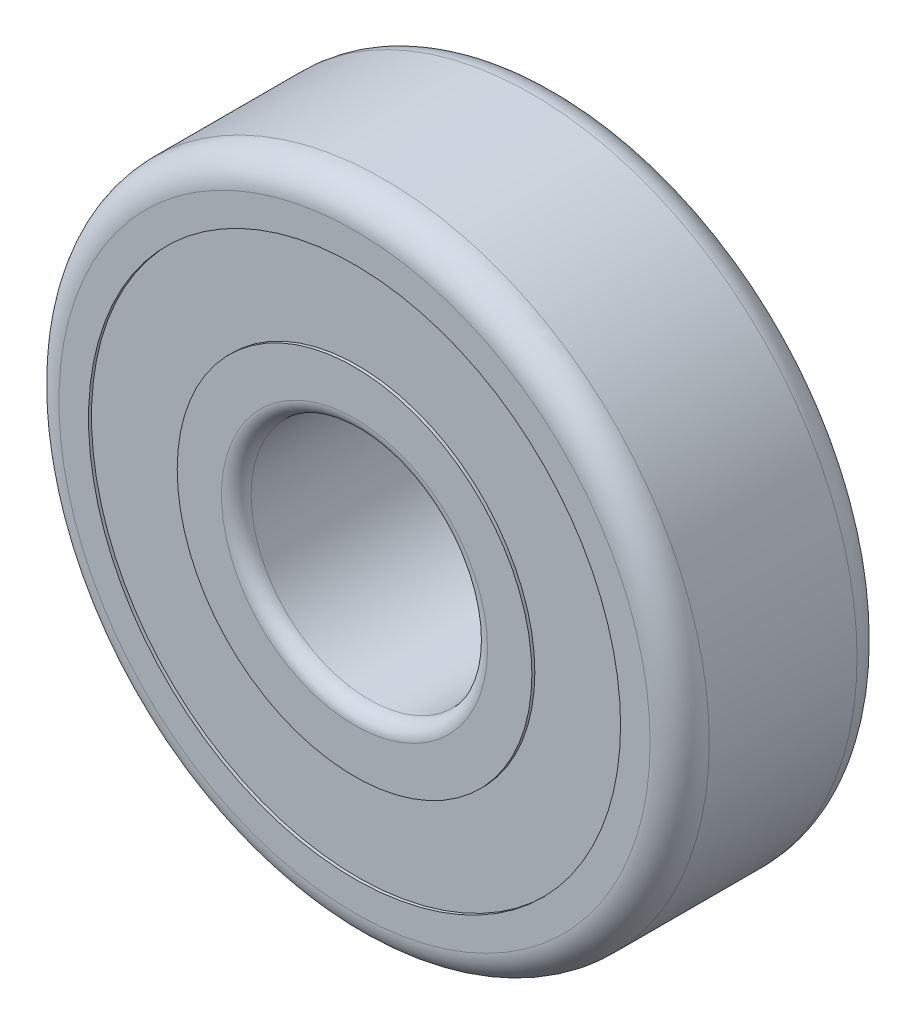
SolidWorks part; units mm, degrees
material "AISI 304"
ref_plane "Front Plane" through (0, 0, 0) normal (0, 0, 1) x (1, 0, 0)
ref_plane "Top Plane" through (0, 0, 0) normal (0, 1, 0) x (1, 0, 0)
ref_plane "Right Plane" through (0, 0, 0) normal (1, 0, 0) x (0, 0, -1)
sketch "Sketch1" plane through (0, 0, 0) normal (0, 0, 1) x (1, 0, 0)
  circle A0 centre (0, 0) radius 11
  circle A1 centre (0, 0) radius 4
  dimension "D1" = 22
  dimension "D2" = 8
extrude "Boss-Extrude1" add sketch "Sketch1" along normal blind 7
fillet "Fillet1" radius 1 1 edges at (11, 0, 7)
fillet "Fillet2" radius 1 1 edges at (11, 0, 0)
fillet "Fillet3" radius 0.5 1 edges at (4, 0, 7)
fillet "Fillet4" radius 0.5 1 edges at (4, 0, 0)
sketch "Sketch2" plane through (0, 0, 7) normal (0, 0, 1) x (1, 0, 0)
  circle A0 centre (0, 0) radius 6
  circle A1 centre (0, 0) radius 9
extrude "Cut-Extrude1" cut sketch "Sketch2" against normal blind 0.1
sketch "Sketch3" plane through (0, 0, 0) normal (0, 0, -1) x (-1, 0, 0)
  circle A0 centre (0, 0) radius 6
  circle A1 centre (0, 0) radius 9.2
extrude "Cut-Extrude2" cut sketch "Sketch3" against normal blind 0.1
